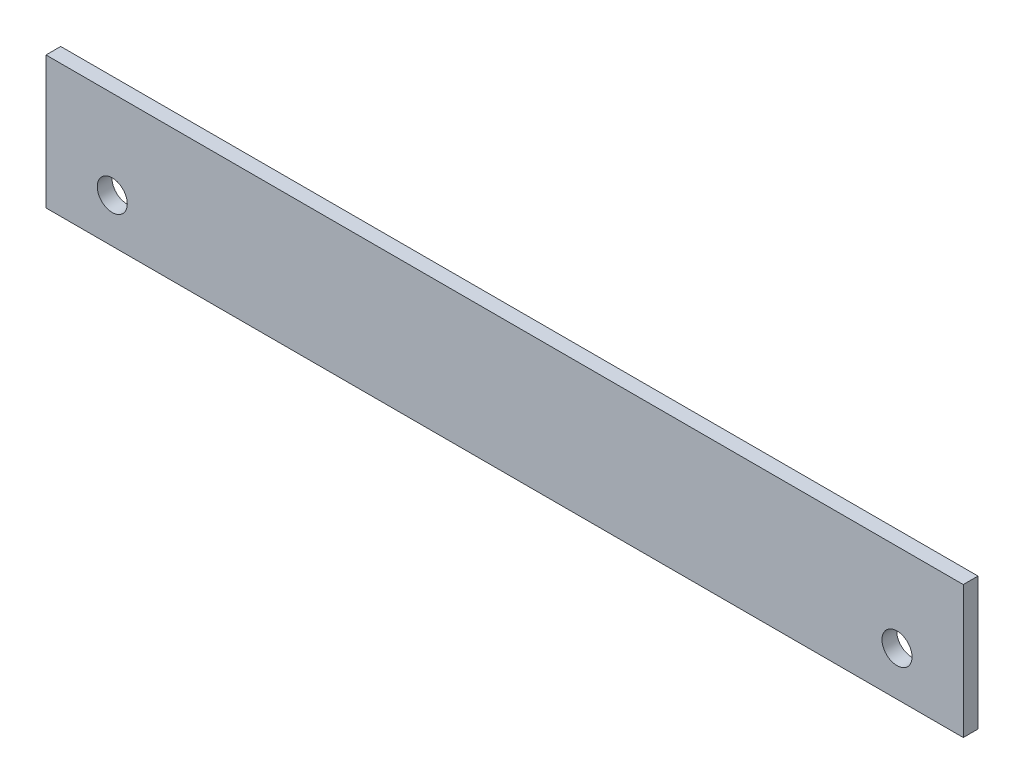
SolidWorks part; units mm, degrees
material "AISI 1020"
ref_plane "Ön Düzlem" through (0, 0, 0) normal (0, 0, 1) x (1, 0, 0)
ref_plane "Üst Düzlem" through (0, 0, 0) normal (0, 1, 0) x (1, 0, 0)
ref_plane "Sağ Düzlem" through (0, 0, 0) normal (1, 0, 0) x (0, 0, -1)
sketch "Sketch1" plane through (0, 0, 0) normal (0, 0, 1) x (1, 0, 0)
  line L1 (155.75, -22.5) -> (-155.75, -22.5)
  line L2 (155.75, -22.5) -> (155.75, 22.5)
  line L3 (155.75, 22.5) -> (-155.75, 22.5)
  line L4 (-155.75, -22.5) -> (-155.75, 22.5)
  line L5 (155.75, -22.5) -> (-155.75, 22.5) construction
  line L6 (155.75, 22.5) -> (-155.75, -22.5) construction
  line L7 (-155.75, 22.5) -> (155.75, 22.5)
  point P0 (0, 0)
  dimension "D1" = 45
  dimension "D2" = 311.5
extrude "Boss-Extrude1" add sketch "Sketch1" along normal mid plane 5 contours L4 L1 L2 L3
hole_wizard "Ø4.6 (4.6) Diameter Hole1" [suppressed] positions "Sketch2" profile "Sketch3" hole size "Ø4.6" standard "ISO"
sketch "Sketch2" plane through (0, 0, 4) normal (0, 0, 1) x (1, 0, 0)
  line L0 (153.25, -22.5) -> (153.25, 22.5) construction
  point P0 (-143.25, 10)
  point P3 (-143.25, -10)
  point P6 (-123.25, -10)
  point P9 (-123.25, 10)
  point P12 (123.25, 10)
  point P15 (143.25, 10)
  point P18 (143.25, -10)
  point P21 (123.25, -10)
  dimension "D1" = 10
  dimension "D2" = 20
  dimension "D3" = 20
  dimension "D4" = 123.25
sketch "Sketch3" plane through (-143.25, 10, 4) normal (1, 0, 0) x (0, -1, 0)
  line L0 (0, 0) -> (0, 8)
  line L1 (0, 8) -> (2.3, 8)
  line L2 (2.3, 8) -> (2.3, 0)
  line L5 (2.3, 0) -> (0, 0)
  line L11 (0, -6.35) -> (0, 107.95) construction
  dimension "Thru Hole Dia." = 4.6
  dimension "Thru Hole Depth" = 8
hole_wizard "Ø10.2 (10.2) Diameter Hole1" positions "Sketch12" profile "Sketch13" hole size "Ø10.2" standard "ISO" end condition through all
sketch "Sketch12" plane through (0, 0, 2.5) normal (0, 0, 1) x (1, 0, 0)
  line L0 (155.75, -22.5) -> (-155.75, -22.5) construction
  line L1 (155.75, -22.5) -> (155.75, 22.5) construction
  line L2 (-155.75, -22.5) -> (-155.75, 22.5) construction
  point P0 (-133.25, -7.5)
  point P2 (133.25, -7.5)
  point P4 (0, 0)
  point P5 (0, 0)
  point P8 (0, 0)
  dimension "D1" = 15
  dimension "D2" = 22.5
  dimension "D3" = 22.5
sketch "Sketch13" plane through (-133.25, -7.5, 2.5) normal (1, 0, 0) x (0, -1, 0)
  line L0 (0, 0) -> (0, 5)
  line L1 (0, 5) -> (5.1, 5)
  line L2 (5.1, 5) -> (5.1, 0)
  line L5 (5.1, 0) -> (0, 0)
  line L11 (0, -6.35) -> (0, 107.95) construction
  dimension "Thru Hole Dia." = 10.2
  dimension "Thru Hole Depth" = 5
fillet "Fillet1" [suppressed] radius 2.5
